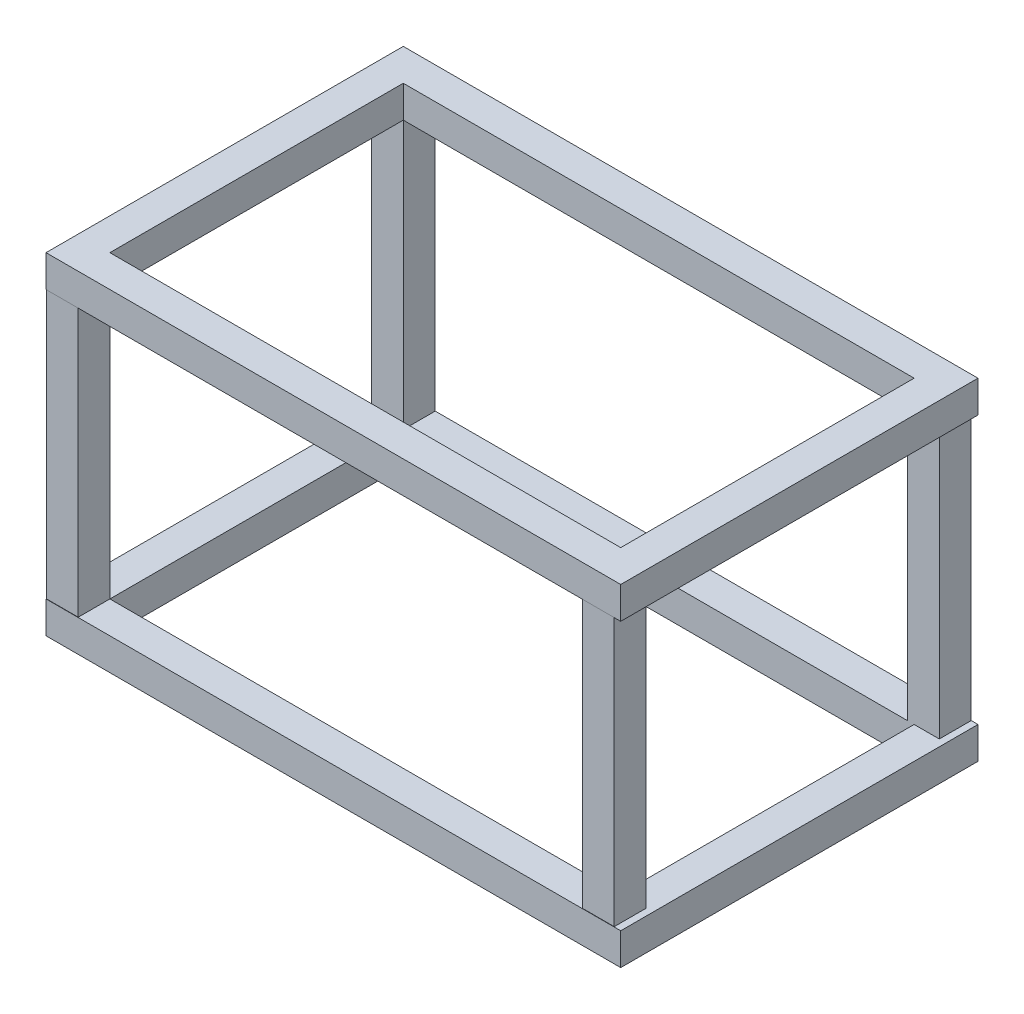
SolidWorks part; units mm, degrees
ref_plane "Front Plane" through (0, 0, 0) normal (0, 0, 1) x (1, 0, 0)
ref_plane "Top Plane" through (0, 0, 0) normal (0, 1, 0) x (1, 0, 0)
ref_plane "Right Plane" through (0, 0, 0) normal (1, 0, 0) x (0, 0, -1)
sketch "Sketch1" plane through (0, 0, 0) normal (0, 1, 0) x (1, 0, 0)
  line L1 (203.2, 116.713) -> (-203.2, 116.713)
  line L2 (203.2, 116.713) -> (203.2, -116.713)
  line L3 (203.2, -116.713) -> (-203.2, -116.713)
  line L4 (-203.2, 116.713) -> (-203.2, -116.713)
  line L5 (203.2, 116.713) -> (-203.2, -116.713) construction
  line L6 (203.2, -116.713) -> (-203.2, 116.713) construction
  line L7 (228.6, 142.113) -> (-228.6, 142.113)
  line L8 (228.6, 142.113) -> (228.6, -142.113)
  line L9 (228.6, -142.113) -> (-228.6, -142.113)
  line L10 (-228.6, 142.113) -> (-228.6, -142.113)
  line L11 (228.6, 142.113) -> (-228.6, -142.113) construction
  line L12 (228.6, -142.113) -> (-228.6, 142.113) construction
  line L13 (-203.2, 116.713) -> (-228.6, 116.713)
  line L14 (-203.2, 116.713) -> (-203.2, 142.113)
  line L15 (-203.2, 142.113) -> (-228.6, 142.113)
  line L16 (-228.6, 116.713) -> (-228.6, 142.113)
  point P0 (0, 0)
  point P6 (0, 0)
  dimension "D1" = 233.426
  dimension "D2" = 406.4
  dimension "D3" = 25.4
extrude "Boss-Extrude1" add sketch "Sketch1" along normal blind 25.4 contours L14 L1 L2 L3 L4 L13 L10 L9 L8 L7 | L13 L14 L7 L10
pattern_linear "LPattern2" count 2 spacing 238.572 along (0, 1, 0) of bodies 101
sketch "Sketch2" plane through (0, 25.4, 0) normal (0, 1, 0) x (1, 0, 0)
  line L1 (-228.6, 142.113) -> (-203.2, 142.113)
  line L2 (-228.6, 142.113) -> (-228.6, 116.713)
  line L3 (-228.6, 116.713) -> (-203.2, 116.713)
  line L4 (-203.2, 142.113) -> (-203.2, 116.713)
extrude "Boss-Extrude2" add sketch "Sketch2" along normal up to surface (213.172 mm away)
pattern_linear "LPattern4" count 2 spacing 426.4 along (1, 0, 0) count 2 spacing 258.572 along (0, 0, 1) of "Boss-Extrude2"
